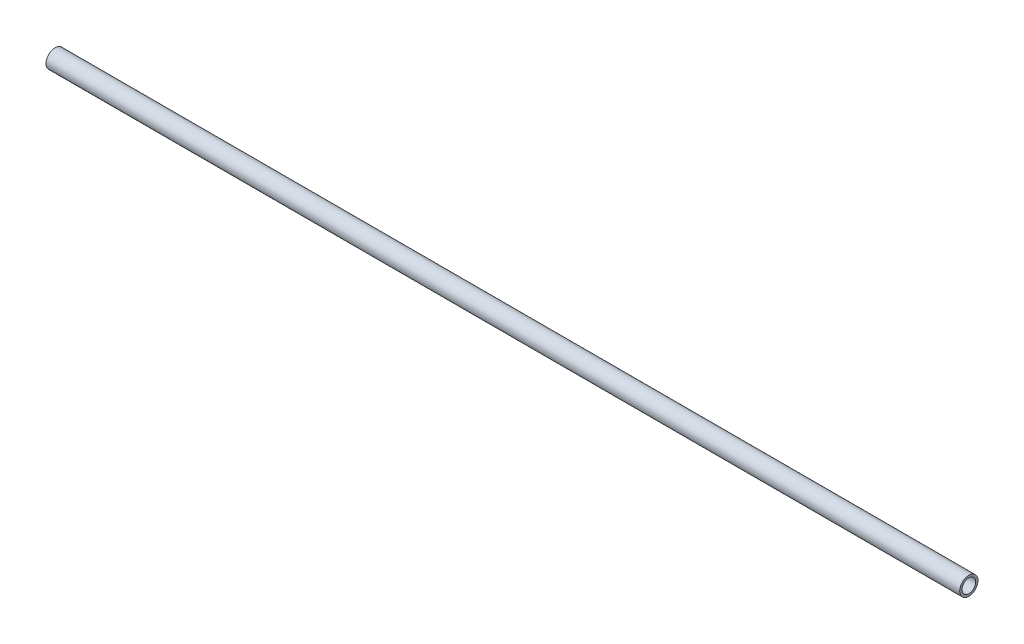
SolidWorks part; units mm, degrees
ref_plane "前视基准面" through (0, 0, 0) normal (0, 0, 1) x (1, 0, 0)
ref_plane "上视基准面" through (0, 0, 0) normal (0, 1, 0) x (1, 0, 0)
ref_plane "右视基准面" through (0, 0, 0) normal (1, 0, 0) x (0, 0, -1)
other "Configuration Table"
sketch "草图1" plane through (0, 0, 0) normal (1, 0, 0) x (0, 0, -1)
  circle A0 centre (0, 0) radius 3
  circle A1 centre (0, 0) radius 4
  dimension "D1" = 6
  dimension "D2" = 8
extrude "凸台-拉伸1" add sketch "草图1" along normal mid plane 400
